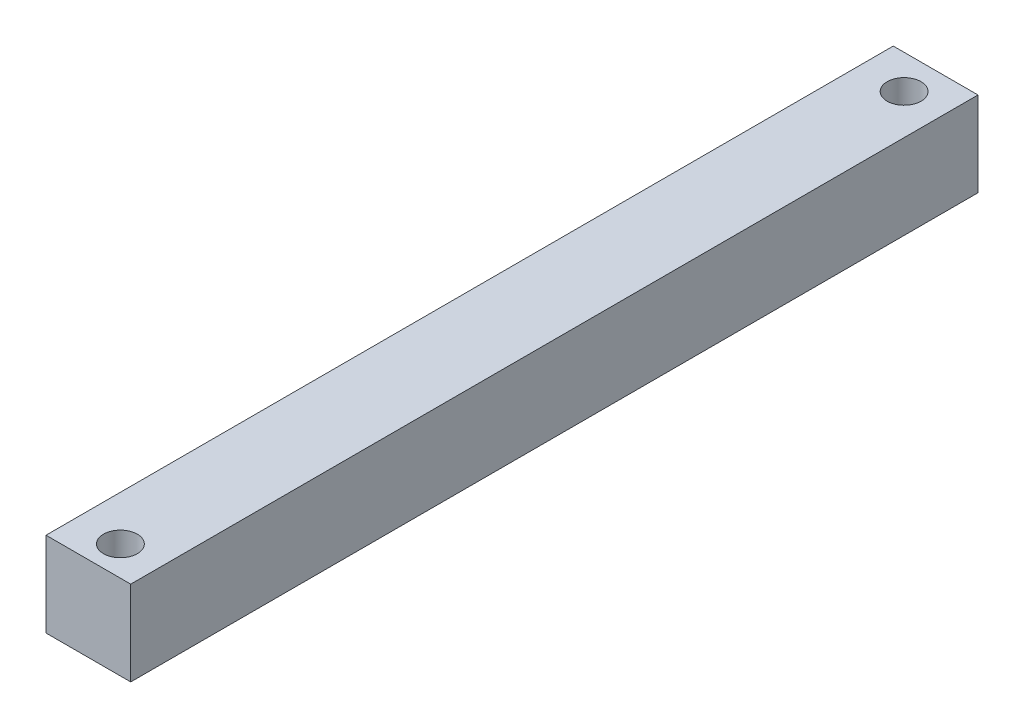
SolidWorks part; units mm, degrees
ref_plane "Front Plane" through (0, 0, 0) normal (0, 0, 1) x (1, 0, 0)
ref_plane "Top Plane" through (0, 0, 0) normal (0, 1, 0) x (1, 0, 0)
ref_plane "Right Plane" through (0, 0, 0) normal (1, 0, 0) x (0, 0, -1)
sketch "Sketch1" plane through (0, 0, 0) normal (0, 1, 0) x (1, 0, 0)
  line L1 (-1.0996, 34.6601) -> (8.9004, 34.6601)
  line L2 (-1.0996, 34.6601) -> (-1.0996, -65.3399)
  line L3 (-1.0996, -65.3399) -> (8.9004, -65.3399)
  line L4 (8.9004, 34.6601) -> (8.9004, -65.3399)
  dimension "D1" = 100
  dimension "D2" = 10
extrude "Boss-Extrude1" add sketch "Sketch1" along normal blind 10
sketch "Sketch2" plane through (0, 10, 0) normal (0, 1, 0) x (1, 0, 0)
  line L0 (8.9004, 34.6601) -> (-1.0996, 34.6601) construction
  circle A0 centre (4.1813, 30.6601) radius 2
  circle A1 centre (4.1813, -61.8399) radius 2
  point P8 (4.4573, 27.8474)
  dimension "D1" = 4
  dimension "D2" = 92.5
extrude "Cut-Extrude1" cut sketch "Sketch2" against normal blind 10
